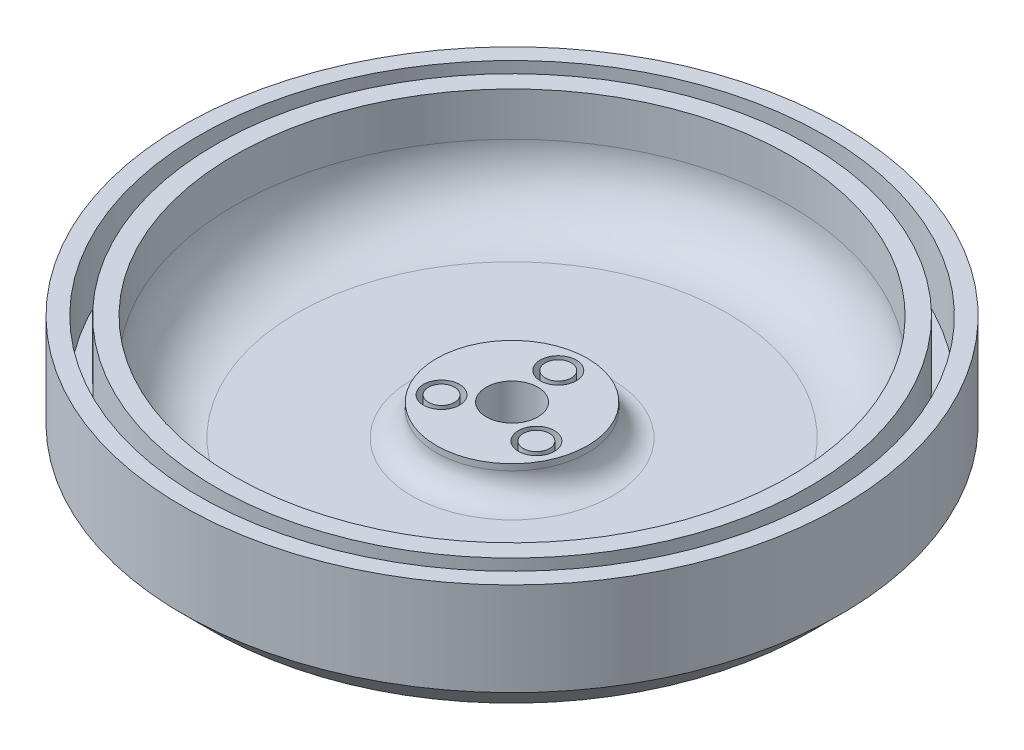
SolidWorks part; units mm, degrees
ref_plane "Front Plane" through (0, 0, 0) normal (0, 0, 1) x (1, 0, 0)
ref_plane "Top Plane" through (0, 0, 0) normal (0, 1, 0) x (1, 0, 0)
ref_plane "Right Plane" through (0, 0, 0) normal (1, 0, 0) x (0, 0, -1)
sketch "Sketch1" plane through (0, 0, 0) normal (0, 0, 1) x (1, 0, 0)
  line L0 (0, 0) -> (0, 63406.6139) construction
  line L1 (-50, 100) -> (-48, 100) construction
  line L2 (-50, 100) -> (-50, 0) construction
  line L3 (-50, 0) -> (-48, 0) construction
  line L4 (-48, 100) -> (-48, 0) construction
  line L5 (-50.3, 10) -> (-50.3, -0.3)
  line L6 (-50.3, -0.3) -> (-47.7, -0.3)
  line L7 (-47.7, 10) -> (-47.7, -0.3)
  line L8 (-50.3, 100) -> (-50.3, -0.3) construction
  line L9 (-47.7, 100) -> (-47.7, -0.3) construction
  line L10 (-50.3, 10) -> (-53, 10)
  line L11 (-53, 10) -> (-53, -5)
  line L12 (-53, -5) -> (-48, -10)
  line L13 (-48, -10) -> (-4.15, -10)
  line L14 (-4.15, -10) -> (-4.15, 7.5741)
  line L15 (-4.15, 7.5741) -> (-7.15, 7.5741)
  line L16 (-7.15, 7.5741) -> (-7.15, 3)
  line L17 (-17.15, -7) -> (-34.7, -7)
  line L18 (-44.7, 3) -> (-44.7, 10)
  line L19 (-44.7, 10) -> (-47.7, 10)
  arc A0 (-7.15, 3) -> (-17.15, -7) centre (-17.15, 3) cw
  arc A1 (-34.7, -7) -> (-44.7, 3) centre (-34.7, 3) cw
  dimension "D14" = 10
  dimension "D1" = 50
  dimension "D2" = 48
  dimension "D3" = 100
  dimension "D5" = 10
  dimension "D6" = 3
  dimension "D7" = 3
  dimension "D8" = 10
  dimension "D9" = 135
  dimension "D10" = 5
  dimension "D11" = 3
  dimension "D12" = 8.3
  dimension "D13" = 3
  dimension "D4" = 0.3
revolve "Revolve1" add sketch "Sketch1" angle 360 about L0
sketch "Sketch3" plane through (0, 7.5741, 0) normal (0, 1, 0) x (1, 0, 0)
  circle A0 centre (0, 0) radius 23.0038
extrude "Cut-Extrude3" cut sketch "Sketch3" against normal up to surface (14.5741 mm away) up to face at (0, -7, -34.7)
sketch "Sketch4" plane through (0, -7, 0) normal (0, 1, 0) x (1, 0, 0)
  circle A0 centre (0, 0) radius 12.15 construction
  circle A1 centre (0, 0) radius 12.15
  circle A2 centre (-6.6878, -4.6579) radius 2.1 construction
  circle A3 centre (-6.6878, -4.6579) radius 2.9 construction
  circle A4 centre (-6.6878, -4.6579) radius 2.1
  circle A5 centre (-6.6878, -4.6579) radius 2.9
  circle A6 centre (0, 0) radius 4.15 construction
  circle A7 centre (0, 0) radius 4.15
  circle A8 centre (-0.69, 8.1207) radius 2.9
  circle A9 centre (-0.69, 8.1207) radius 2.1
  circle A10 centre (7.3778, -3.4628) radius 2.9
  circle A11 centre (7.3778, -3.4628) radius 2.1
  point P23 (0, 0)
  circle M10 centre (0, 0) radius 4.15
  dimension "D1" = 3
extrude "Boss-Extrude1" add sketch "Sketch4" along normal blind 5 contours A1 A10 A8 A5 M10 | A4 | A11 | A9
fillet "Fillet1" radius 4 1 edges at (0, -7, -12.15)
